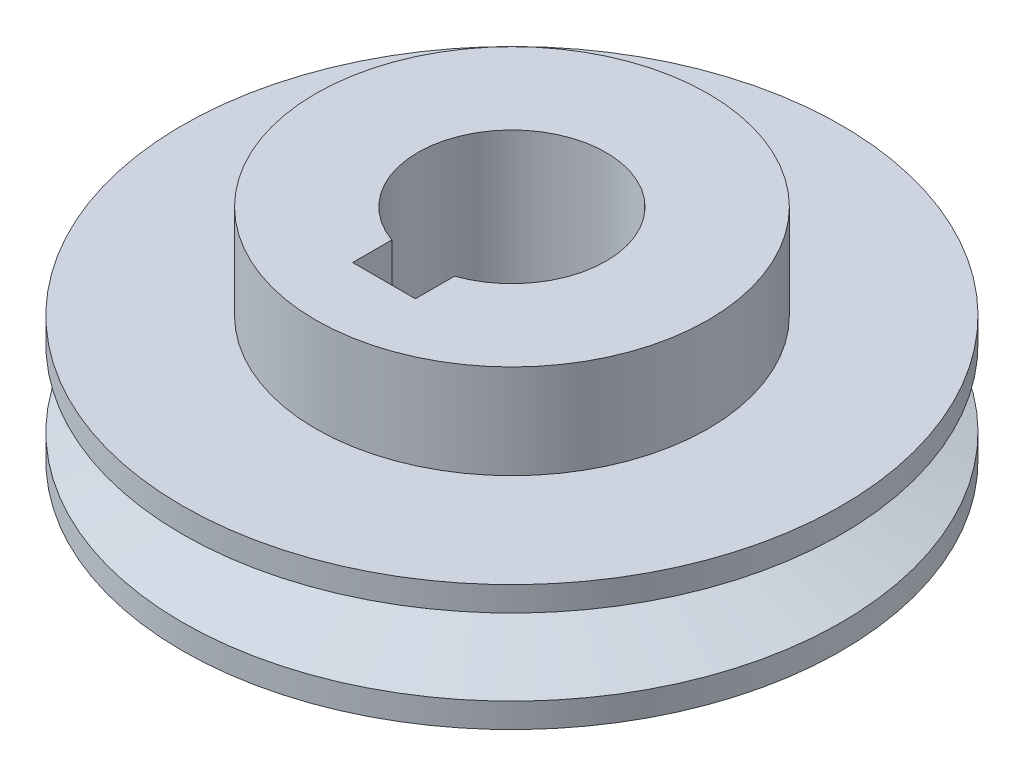
SolidWorks part; units mm, degrees
ref_plane "Front Plane" through (0, 0, 0) normal (0, 0, 1) x (1, 0, 0)
ref_plane "Top Plane" through (0, 0, 0) normal (0, 1, 0) x (1, 0, 0)
ref_plane "Right Plane" through (0, 0, 0) normal (1, 0, 0) x (0, 0, -1)
sketch "Sketch1" plane through (0, 0, 0) normal (0, 0, 1) x (1, 0, 0)
  line L0 (0, 48.3675) -> (0, 0) construction
  line L1 (-12, 0) -> (-42, 0)
  line L2 (-42, 0) -> (-42, 3.1385)
  line L3 (-42, 3.1385) -> (-31, 6.5016)
  line L4 (-31, 6.5016) -> (-31, 9.4984)
  line L5 (-31, 9.4984) -> (-42, 12.8615)
  line L6 (-42, 12.8615) -> (-42, 16)
  line L7 (-42, 16) -> (-25, 16)
  line L8 (-25, 16) -> (-25, 28)
  line L9 (-25, 28) -> (-12, 28)
  line L10 (-12, 28) -> (-12, 0)
  line L11 (-40, 15.587) -> (-40, -1.7066) construction
  line L12 (-46.3498, 8) -> (0, 8) construction
  point P17 (-31, 8)
  point P18 (-40, 3.75)
  point P27 (-40, 12.25)
  dimension "D1" = 80
  dimension "D2" = 8
  dimension "D3" = 9
  dimension "D4" = 34
  dimension "D5" = 2
  dimension "D6" = 8.5
  dimension "D7" = 24
  dimension "D9" = 12
  dimension "D8" = 50
revolve "Revolve1" add sketch "Sketch1" angle 360 about L0
sketch "Sketch2" plane through (0, 0, 0) normal (0, 1, 0) x (1, 0, 0)
  line L0 (0, 0) -> (0, -16.3) construction
  line L2 (-4, -16.3) -> (4, -16.3)
  line L3 (-4, -16.3) -> (-4, 0)
  line L4 (-4, 0) -> (4, 0)
  line L5 (4, -16.3) -> (4, 0)
  dimension "D1" = 8
  dimension "D2" = 16.3
extrude "Cut-Extrude1" cut sketch "Sketch2" along normal through all both and the other way through all contours L3 L2 L5 L4
equation "\"dd\"=80"
equation "\"D1@Sketch1\"=\"dd\""
equation "\"f_poulie_motrice\"=8"
equation "\"D2@Sketch1\"=\"f_poulie_motrice\""
equation "\"h_gorge_poulie_motrice\"= 9"
equation "\"angle_poulie_motrice\"=34"
equation "\"D4@Sketch1\"=\"angle_poulie_motrice\""
equation "\"D3@Sketch1\"=\"h_gorge_poulie_motrice\""
equation "\"b_gorge_poulie_motrice\"=2"
equation "\"D5@Sketch1\"=\"b_gorge_poulie_motrice\""
equation "\"w_gorge_poulie_motrice\"=8.5"
equation "\"D6@Sketch1\"=\"w_gorge_poulie_motrice\""
